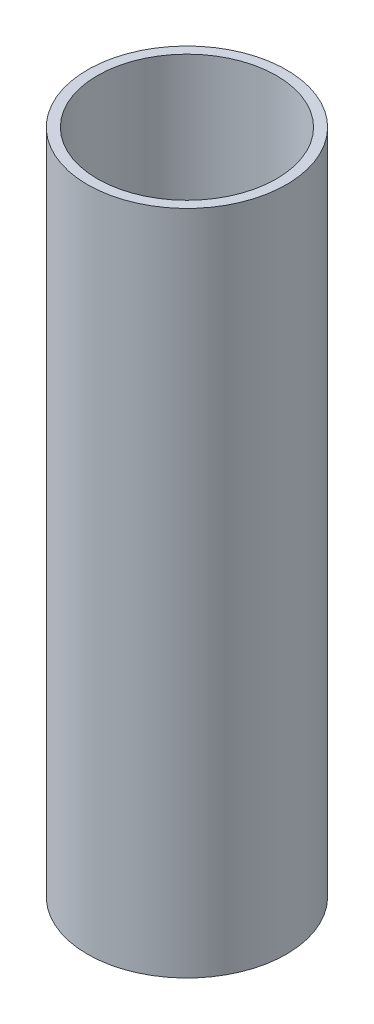
SolidWorks part; units mm, degrees
material "Thornel Mat VMA"
ref_plane "前视基准面" through (0, 0, 0) normal (0, 0, 1) x (1, 0, 0)
ref_plane "上视基准面" through (0, 0, 0) normal (0, 1, 0) x (1, 0, 0)
ref_plane "右视基准面" through (0, 0, 0) normal (1, 0, 0) x (0, 0, -1)
sketch "草图1" plane through (0, 0, 0) normal (0, 1, 0) x (1, 0, 0)
  circle A0 centre (0, 0) radius 10
  circle A1 centre (0, 0) radius 9
  dimension "D1" = 20
  dimension "D2" = 18
extrude "凸台-拉伸1" add sketch "草图1" along normal blind 67
